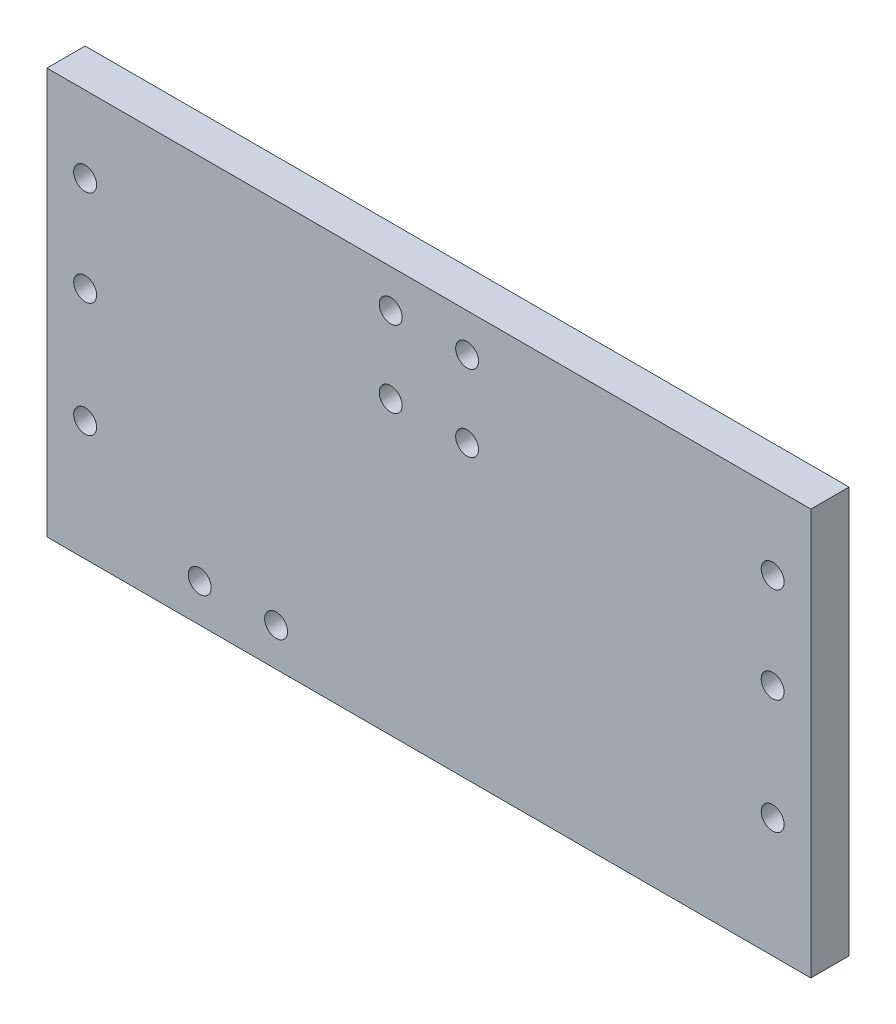
SolidWorks part; units mm, degrees
ref_plane "Front Plane" through (0, 0, 0) normal (0, 0, 1) x (1, 0, 0)
ref_plane "Top Plane" through (0, 0, 0) normal (0, 1, 0) x (1, 0, 0)
ref_plane "Right Plane" through (0, 0, 0) normal (1, 0, 0) x (0, 0, -1)
sketch "Sketch1" plane through (0, 0, 0) normal (0, 0, 1) x (1, 0, 0)
  line L1 (-50, -26.58) -> (50, -26.58)
  line L2 (-50, -26.58) -> (-50, 26.58)
  line L3 (-50, 26.58) -> (50, 26.58)
  line L4 (50, -26.58) -> (50, 26.58)
  line L5 (-50, -26.58) -> (50, 26.58) construction
  line L6 (-50, 26.58) -> (50, -26.58) construction
  point P0 (0, 0)
  dimension "D1" = 100
  dimension "D2" = 53.16
extrude "Boss-Extrude1" add sketch "Sketch1" along normal blind 5
sketch "Sketch2" plane through (0, 0, 5) normal (0, 0, 1) x (1, 0, 0)
  line L0 (50, 26.58) -> (-50, 26.58) construction
  line L1 (-50, 26.58) -> (-50, -26.58) construction
  line L2 (-50, -26.58) -> (50, -26.58) construction
  line L3 (0, -2.75) -> (0, 2.75) construction
  circle A0 centre (-45, 16.58) radius 1.5
  circle A1 centre (-45, 4.08) radius 1.5
  circle A2 centre (-45, -10.92) radius 1.5
  circle A6 centre (45, -10.92) radius 1.5
  circle A7 centre (45, 4.08) radius 1.5
  circle A8 centre (45, 16.58) radius 1.5
  circle A9 centre (-5, 11.58) radius 1.5
  circle A10 centre (-5, 21.58) radius 1.5
  circle A11 centre (5, 11.58) radius 1.5
  circle A12 centre (5, 21.58) radius 1.5
  circle A13 centre (-30, -21.58) radius 1.5
  circle A14 centre (-20, -21.58) radius 1.5
  point P30 (0, 0)
  dimension "D3" = 3
  dimension "D4" = 3
  dimension "D5" = 3
  dimension "D7" = 37.5
  dimension "D8" = 3
  dimension "D9" = 5
  dimension "D11" = 3
  dimension "D13" = 3
  dimension "D14" = 3
  dimension "D1" = 10
  dimension "D2" = 12.5
  dimension "D6" = 5
  dimension "D10" = 10
  dimension "D12" = 5
  dimension "D15" = 5
  dimension "D16" = 20
  dimension "D17" = 10
extrude "Cut-Extrude1" cut sketch "Sketch2" against normal through all
